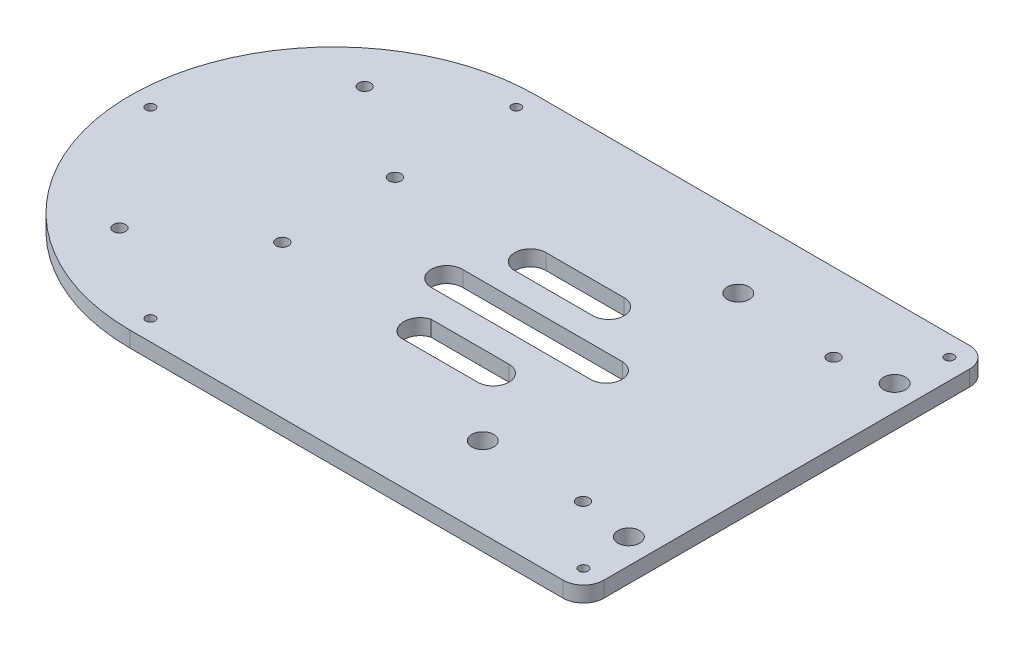
SolidWorks part; units mm, degrees
ref_plane "Front Plane" through (0, 0, 0) normal (0, 0, 1) x (1, 0, 0)
ref_plane "Top Plane" through (0, 0, 0) normal (0, 1, 0) x (1, 0, 0)
ref_plane "Right Plane" through (0, 0, 0) normal (1, 0, 0) x (0, 0, -1)
sketch "Sketch1" plane through (0, 0, 0) normal (0, 1, 0) x (1, 0, 0)
  line L0 (-133.1666, -1.5808) -> (76.8365, -1.5808) construction
  line L1 (76.8365, 56.9192) -> (76.8365, -60.0808)
  line L2 (70.3365, 63.4192) -> (-68.1635, 63.4192)
  line L4 (-31.6635, 3.4192) -> (19.3365, 3.4192)
  line L7 (-23.1635, 21.4192) -> (1.8365, 21.4192)
  line L8 (-23.1635, 11.4192) -> (1.8365, 11.4192)
  line L11 (-23.1666, -25.4197) -> (1.8334, -25.4197)
  line L12 (-23.1666, -15.4197) -> (1.8334, -15.4197)
  line L13 (-32.0941, -6.5808) -> (18.9059, -6.5808)
  line L14 (70.3365, -66.5808) -> (-68.1635, -66.5808)
  arc A0 (70.3365, 63.4192) -> (76.8365, 56.9192) centre (70.3365, 56.9192) cw
  circle A3 centre (18.8365, 40.9193) radius 3.5
  circle A4 centre (51.8365, 38.4192) radius 1.95
  circle A5 centre (68.8365, 40.9193) radius 3.5
  circle A7 centre (70.3365, 56.9192) radius 1.475
  arc A8 (1.8334, -25.4197) -> (1.8334, -15.4197) centre (1.8334, -20.4197) ccw
  arc A10 (70.3365, -66.5808) -> (76.8365, -60.0808) centre (70.3365, -60.0808) ccw
  circle A11 centre (18.8365, -40.8007) radius 3.5
  circle A12 centre (70.3365, -60.0808) radius 1.475
  circle A13 centre (51.6855, -41.5807) radius 1.95
  circle A14 centre (68.8365, -44.0807) radius 3.5
  arc A17 (19.3365, 3.4192) -> (18.9059, -6.5808) centre (19.1212, -1.5808) cw
  arc A18 (-31.6635, 3.4192) -> (-32.0941, -6.5808) centre (-31.8788, -1.5808) ccw
  arc A19 (-68.1635, 63.4192) -> (-68.1635, -66.5808) centre (-68.1666, -1.5808) ccw
  circle A20 centre (-68.1635, 56.9192) radius 1.475
  circle A21 centre (-98.1635, 38.4192) radius 1.95
  circle A22 centre (-68.1635, 18.1096) radius 1.975
  circle A23 centre (-68.1635, -17.8904) radius 1.975
  circle A24 centre (-98.1635, -40) radius 1.95
  circle A25 centre (-68.1635, -60.0808) radius 1.475
  circle A26 centre (-126.6635, -1.5808) radius 1.475
  arc A28 (1.8365, 21.4192) -> (1.8365, 11.4192) centre (1.8365, 16.4192) cw
  arc A29 (-23.1666, -15.4197) -> (-23.1666, -25.4197) centre (-21.5232, -20.4197) ccw
  arc A30 (-23.1635, 21.4192) -> (-23.1635, 11.4192) centre (-23.1635, 16.4192) ccw
  point P43 (76.8365, -1.5808)
  dimension "D3" = 6.5
  dimension "D7" = 36.5
  dimension "D8" = 8
  dimension "D12" = 7
  dimension "D13" = 3.9
  dimension "D14" = 7
  dimension "D15" = 130
  dimension "D17" = 65
  dimension "D21" = 2.95
  dimension "D23" = 6.5
  dimension "D27" = 3.95
  dimension "D28" = 36
  dimension "D25" = 5
  dimension "D30" = 6.5
  dimension "D31" = 6.5
  dimension "D32" = 6.5
  dimension "D11" = 6.5
  dimension "D2" = 145
  dimension "D4" = 51
  dimension "D5" = 8
  dimension "D6" = 50
  dimension "D9" = 6.5
  dimension "D10" = 25
  dimension "D16" = 50
  dimension "D18" = 85
  dimension "D19" = 80
  dimension "D20" = 117
  dimension "D22" = 138.5
  dimension "D24" = 150
  dimension "D26" = 25
  dimension "D29" = 58.5
extrude "Boss-Extrude2" add sketch "Sketch1" along normal blind 5
